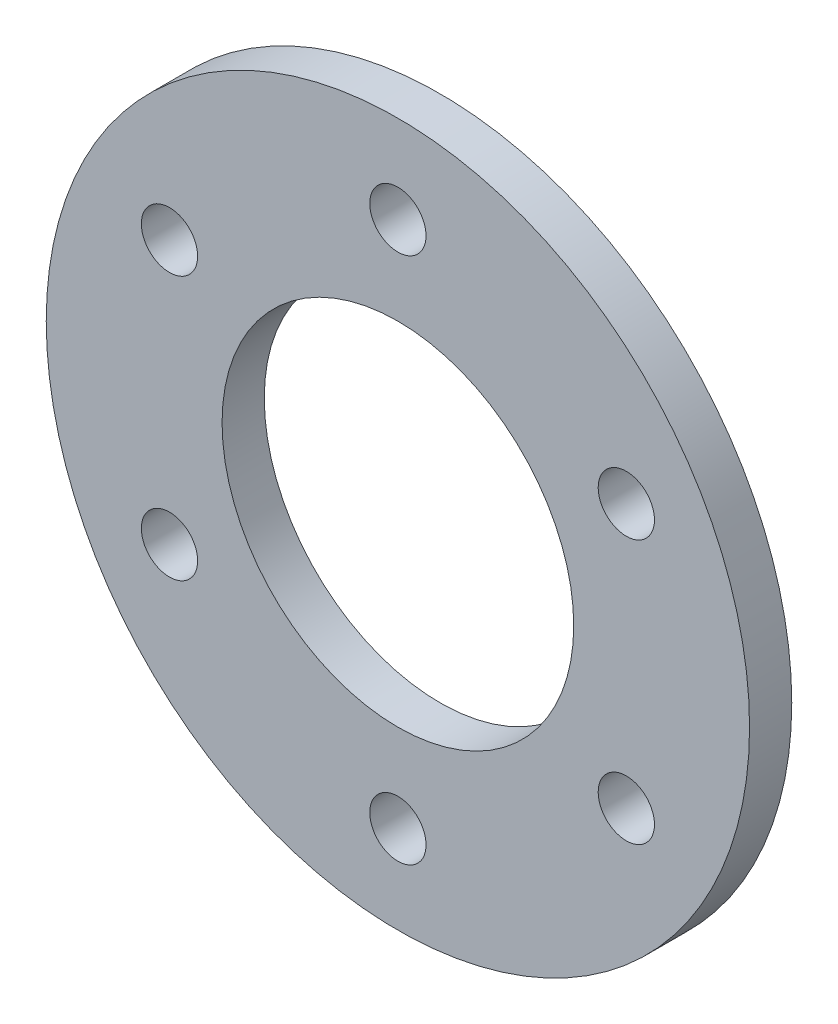
SolidWorks part; units mm, degrees
ref_plane "Front Plane" through (0, 0, 0) normal (0, 0, 1) x (1, 0, 0)
ref_plane "Top Plane" through (0, 0, 0) normal (0, 1, 0) x (1, 0, 0)
ref_plane "Right Plane" through (0, 0, 0) normal (1, 0, 0) x (0, 0, -1)
sketch "Sketch1" plane through (0, 0, 0) normal (0, 0, 1) x (1, 0, 0)
  circle A0 centre (0, 0) radius 25
  dimension "D1" = 50
extrude "Boss-Extrude1" add sketch "Sketch1" along normal blind 3 contours A0
sketch "Sketch4" plane through (0, 0, 0) normal (0, 0, -1) x (-1, 0, 0)
  circle A0 centre (0, 0) radius 12.5
extrude "Cut-Extrude1" cut sketch "Sketch4" against normal blind 8.2
sketch "Sketch11" plane through (0, 0, 0) normal (0, 0, -1) x (-1, 0, 0)
  line L1 (0, 7.5) -> (0, 18.75) construction
  circle A4 centre (0, 18.75) radius 2
  circle A5 centre (16.238, 9.375) radius 2
  circle A6 centre (16.238, -9.375) radius 2
  circle A7 centre (0, -18.75) radius 2
  circle A8 centre (-16.238, -9.375) radius 2
  circle A9 centre (-16.238, 9.375) radius 2
  point P20 (0, 0)
  dimension "D1" = 11.25
  dimension "D3" = 4
  dimension "D4" = 6
extrude "Cut-Extrude2" cut sketch "Sketch11" against normal blind 10
sketch "Sketch12" plane through (0, 0, 0) normal (0, 0, 1) x (1, 0, 0)
  circle A0 centre (0, 0) radius 12.5
